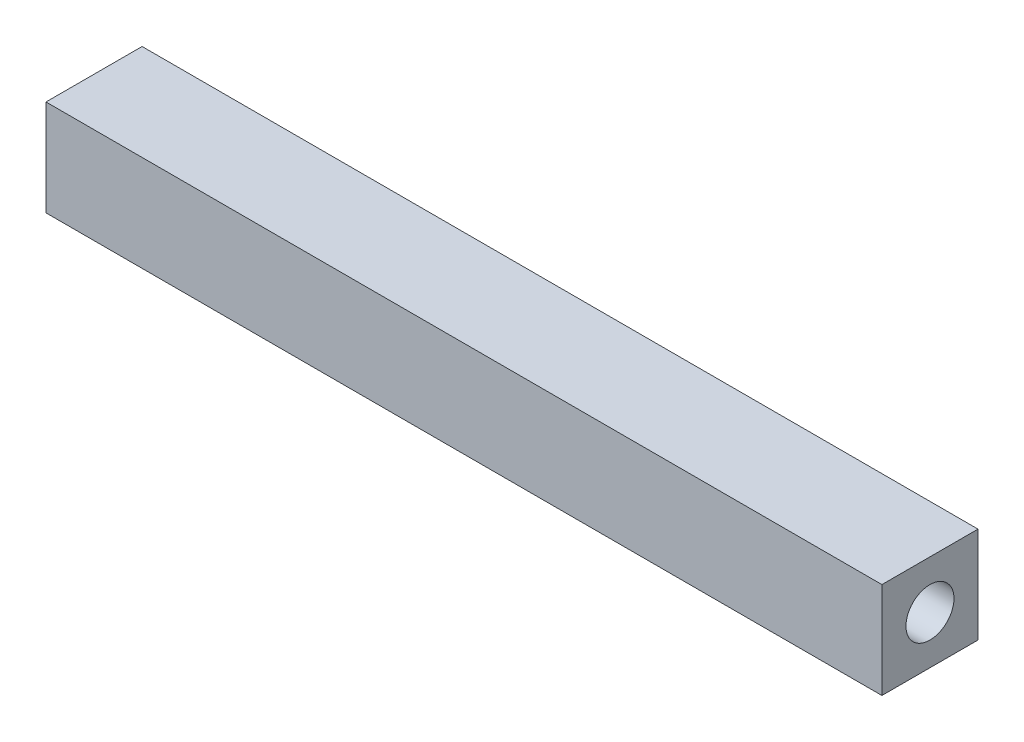
SolidWorks part; units mm, degrees
ref_plane "Front Plane" through (0, 0, 0) normal (0, 0, 1) x (1, 0, 0)
ref_plane "Top Plane" through (0, 0, 0) normal (0, 1, 0) x (1, 0, 0)
ref_plane "Right Plane" through (0, 0, 0) normal (1, 0, 0) x (0, 0, -1)
sketch "Sketch1" plane through (0, 0, 0) normal (0, 1, 0) x (1, 0, 0)
  line L1 (-43.5, -5) -> (43.5, -5)
  line L2 (-43.5, -5) -> (-43.5, 5)
  line L3 (-43.5, 5) -> (43.5, 5)
  line L4 (43.5, -5) -> (43.5, 5)
  line L5 (-43.5, -5) -> (43.5, 5) construction
  line L6 (-43.5, 5) -> (43.5, -5) construction
  point P0 (0, 0)
  dimension "D1" = 10
  dimension "D2" = 87
extrude "Boss-Extrude1" add sketch "Sketch1" along normal blind 10
sketch "Sketch2" plane through (43.5, 0, 0) normal (1, 0, 0) x (0, 0, -1)
  line L0 (0, 0) -> (0, 10) construction
  line L1 (-5, 0) -> (5, 0) construction
  line L2 (-5, 10) -> (5, 10) construction
  line L3 (0, 10) -> (-5, 5) construction
  line L4 (-5, 10) -> (-5, 0) construction
  line L5 (-5, 5) -> (5, 5) construction
  line L6 (5, 10) -> (5, 0) construction
  circle A0 centre (0, 5) radius 2.5
  dimension "D1" = 5
extrude "Cut-Extrude1" cut sketch "Sketch2" against normal blind 4 contours A0
mirror "Mirror1" about plane through (0, 0, 0) normal (1, 0, 0) of "Cut-Extrude1"
